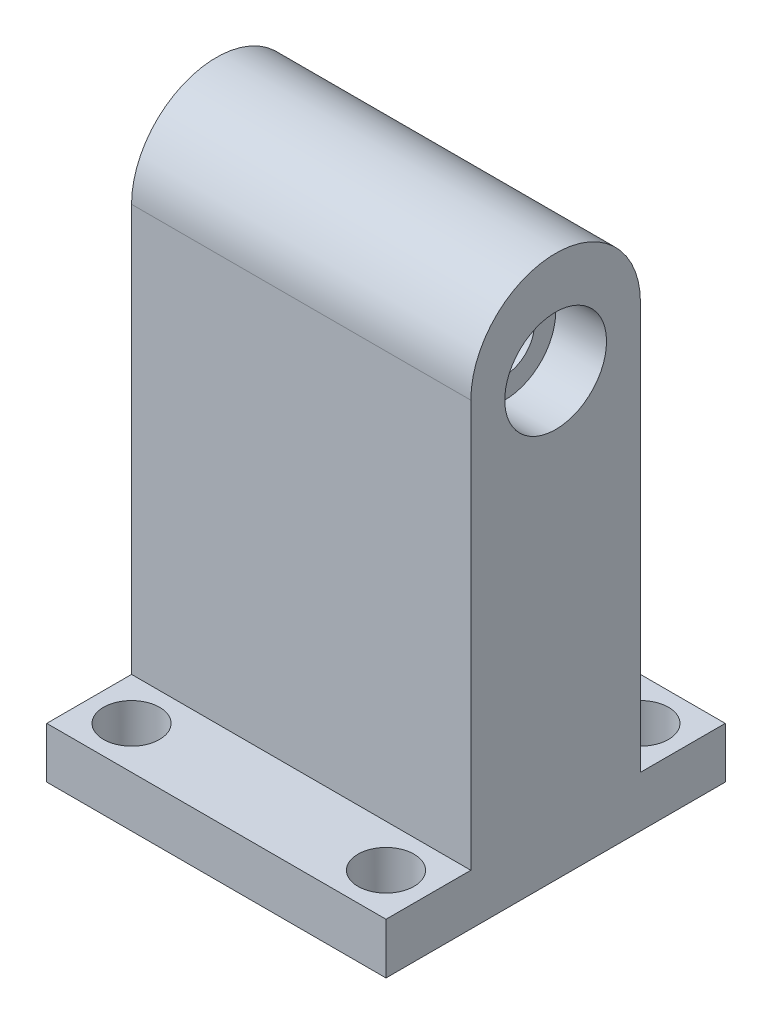
SolidWorks part; units mm, degrees
ref_plane "Front Plane" through (0, 0, 0) normal (0, 0, 1) x (1, 0, 0)
ref_plane "Top Plane" through (0, 0, 0) normal (0, 1, 0) x (1, 0, 0)
ref_plane "Right Plane" through (0, 0, 0) normal (1, 0, 0) x (0, 0, -1)
sketch "Sketch1" plane through (0, 0, 0) normal (0, 1, 0) x (1, 0, 0)
  line L1 (-10, 10) -> (10, 10)
  line L2 (-10, 10) -> (-10, -10)
  line L3 (-10, -10) -> (10, -10)
  line L4 (10, 10) -> (10, -10)
  line L5 (-10, 10) -> (10, -10) construction
  line L6 (-10, -10) -> (10, 10) construction
  point P0 (0, 0)
  dimension "D1" = 20
  dimension "D2" = 20
extrude "Boss-Extrude1" add sketch "Sketch1" along normal blind 36
sketch "Sketch2" plane through (10, 0, 0) normal (1, 0, 0) x (0, 0, -1)
  line L0 (0, 55) -> (0, -55) construction
  line L1 (-10, 36) -> (10, 36) construction
  circle A0 centre (0, 26) radius 3
  dimension "D1" = 6
  dimension "D2" = 10
extrude "Cut-Extrude1" cut sketch "Sketch2" against normal blind 3
sketch "Sketch3" plane through (7, 0, 0) normal (1, 0, 0) x (0, 0, -1)
  circle A0 centre (0, 26) radius 1.75
  dimension "D1" = 3.5
extrude "Cut-Extrude2" cut sketch "Sketch3" against normal through all
sketch "Sketch4" plane through (-10, 0, 0) normal (-1, 0, 0) x (0, 0, 1)
  circle A0 centre (0, 26) radius 3
  dimension "D1" = 6
extrude "Cut-Extrude3" cut sketch "Sketch4" against normal blind 3
sketch "Sketch5" plane through (0, 36, 0) normal (0, 1, 0) x (1, 0, 0)
  line L0 (-10, 10) -> (-10, -10) construction
  line L1 (10, 10) -> (-10, 10) construction
  line L2 (-10, -10) -> (10, -10) construction
  line L3 (10, -10) -> (10, 10) construction
  circle A0 centre (-7.5, 7.5) radius 1.6496
  circle A1 centre (7.5, 7.5) radius 1.6496
  circle A2 centre (7.5, -7.5) radius 1.6496
  circle A3 centre (-7.5, -7.5) radius 1.6496
  point P8 (0, 0)
  point P9 (0, 0)
  point P10 (0, 0)
  point P11 (0, 0)
  dimension "D1" = 2.5
  dimension "D2" = 2.5
  dimension "D3" = 2.5
  dimension "D4" = 2.5
extrude "Cut-Extrude4" cut sketch "Sketch5" against normal through all
sketch "Sketch6" plane through (-10, 0, 0) normal (-1, 0, 0) x (0, 0, 1)
  line L0 (0, 0) -> (0, 3) construction
  line L1 (0, -11) -> (0, 11) construction
  line L2 (-10, 3) -> (-5, 3)
  line L3 (-10, 36) -> (-10, 0) construction
  line L4 (-5, 3) -> (-5, 27)
  line L5 (5, 27) -> (5, 3)
  line L6 (5, 3) -> (10, 3)
  line L7 (10, 36) -> (10, 0) construction
  line L8 (-10, 3) -> (-10, 36)
  line L9 (-10, 36) -> (10, 36)
  line L10 (10, 36) -> (10, 3)
  arc A0 (-5, 27) -> (5, 27) centre (0, 27) cw
  point P17 (0, 32)
  dimension "D4" = 32
  dimension "D1" = 3
  dimension "D2" = 5
  dimension "D3" = 5
extrude "Cut-Extrude5" cut sketch "Sketch6" against normal through all
